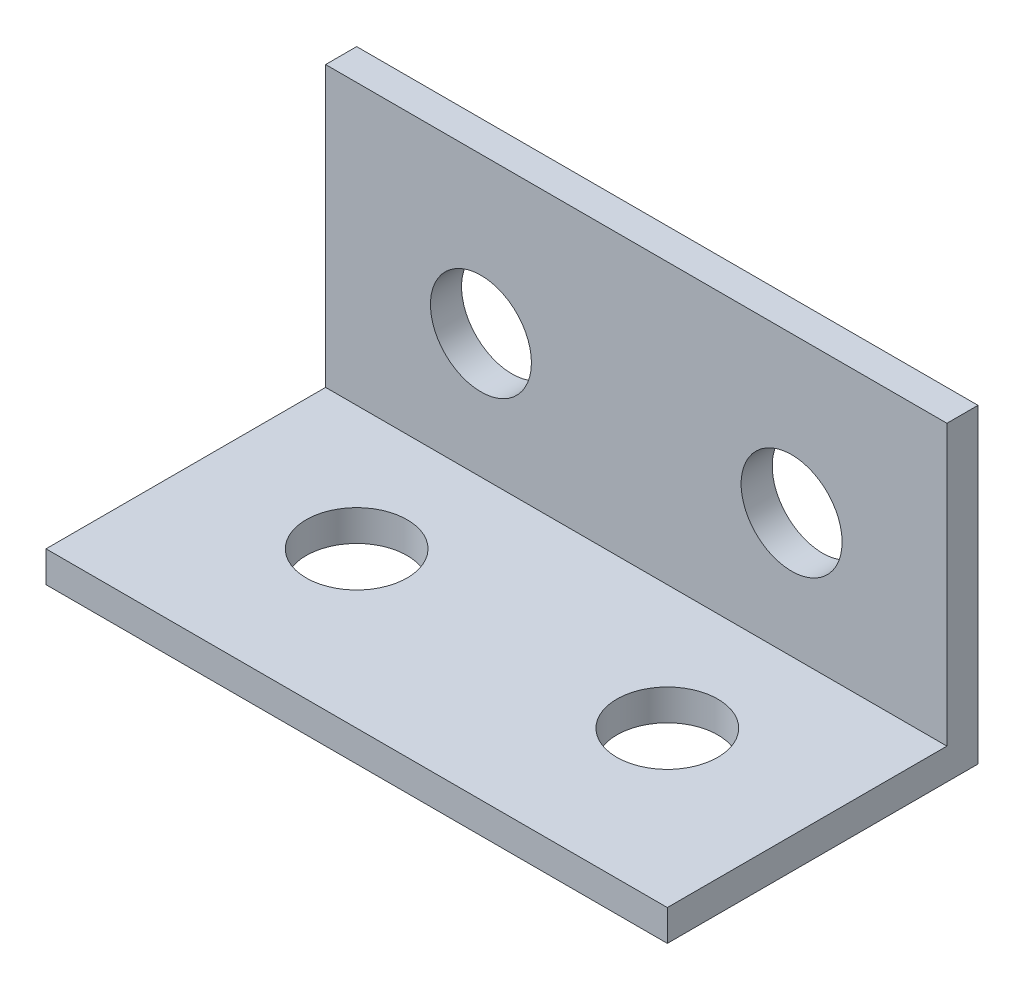
SolidWorks part; units mm, degrees
material "Cast Stainless Steel"
ref_plane "Front Plane" through (0, 0, 0) normal (0, 0, 1) x (1, 0, 0)
ref_plane "Top Plane" through (0, 0, 0) normal (0, 1, 0) x (1, 0, 0)
ref_plane "Right Plane" through (0, 0, 0) normal (1, 0, 0) x (0, 0, -1)
sketch "Sketch1" plane through (0, 0, 0) normal (0, 0, 1) x (1, 0, 0)
  line L0 (0, 10) -> (20, 10) construction
  line L1 (0, 0) -> (40, 0)
  line L2 (0, 0) -> (0, 20)
  line L3 (0, 20) -> (40, 20)
  line L4 (40, 0) -> (40, 20)
  line L5 (20, 10) -> (40, 10) construction
  circle A0 centre (10, 10) radius 3.25
  circle A1 centre (30, 10) radius 3.25
  dimension "D3" = 6.5
  dimension "D4" = 6.5
  dimension "D1" = 40
  dimension "D2" = 20
extrude "Boss-Extrude1" add sketch "Sketch1" along normal blind 2
sketch "Sketch3" plane through (0, 0, 0) normal (0, 1, 0) x (1, 0, 0)
  line L0 (0, -10) -> (20, -10) construction
  line L1 (0, 0) -> (40, 0)
  line L2 (0, 0) -> (0, -20)
  line L3 (0, -20) -> (40, -20)
  line L4 (40, 0) -> (40, -20)
  line L5 (20, -10) -> (40, -10) construction
  circle A0 centre (10, -10) radius 3.25
  circle A1 centre (30, -10) radius 3.25
  dimension "D2" = 6.5
  dimension "D1" = 20
extrude "Boss-Extrude2" add sketch "Sketch3" along normal blind 2
